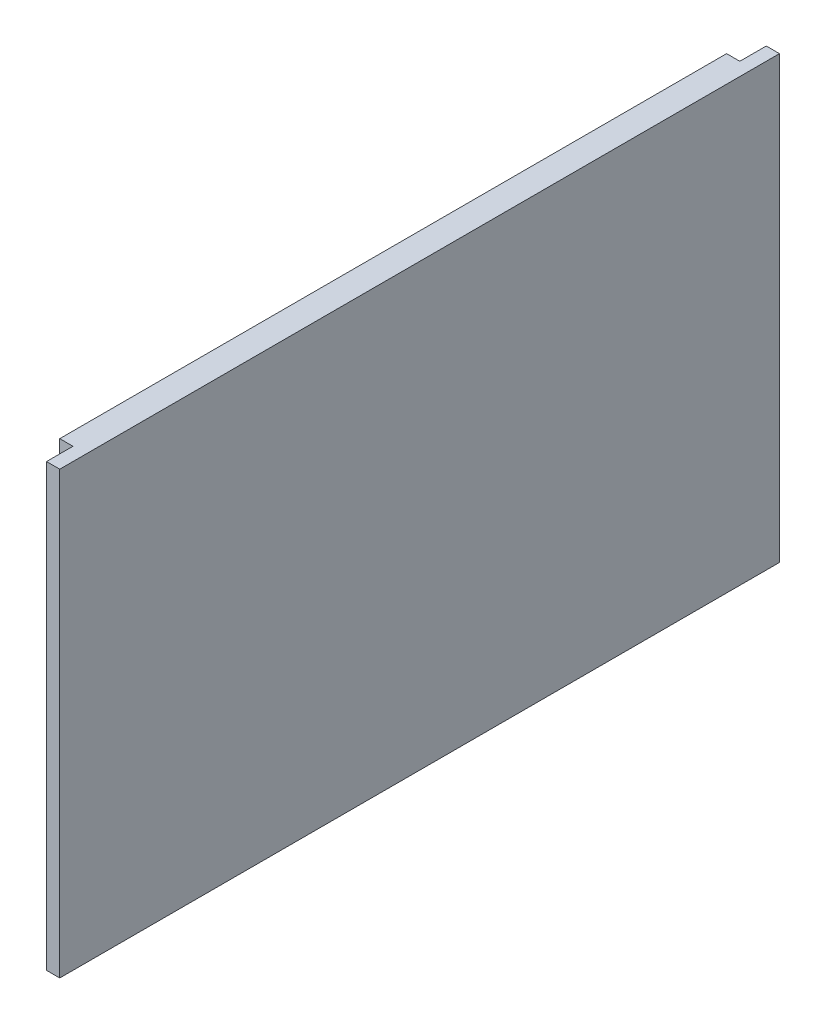
SolidWorks part; units mm, degrees
ref_plane "Front Plane" through (0, 0, 0) normal (0, 0, 1) x (1, 0, 0)
ref_plane "Top Plane" through (0, 0, 0) normal (0, 1, 0) x (1, 0, 0)
ref_plane "Right Plane" through (0, 0, 0) normal (1, 0, 0) x (0, 0, -1)
sketch "Sketch1" plane through (0, 0, 0) normal (1, 0, 0) x (0, 0, -1)
  line L1 (0, 0) -> (490, 0)
  line L2 (0, 0) -> (0, 300)
  line L3 (0, 300) -> (490, 300)
  line L4 (490, 0) -> (490, 300)
  dimension "D1" = 490
  dimension "D2" = 300
extrude "Boss-Extrude1" add sketch "Sketch1" along normal blind 18
sketch "Sketch5" plane through (0, 0, 0) normal (0, 0, 1) x (1, 0, 0)
  line L0 (18, 0) -> (0, 0) construction
  line L1 (0, 300) -> (9, 300)
  line L2 (0, 300) -> (0, 0)
  line L3 (0, 0) -> (9, 0)
  line L4 (9, 300) -> (9, 0)
  dimension "D1" = 9
extrude "Cut-Extrude1" cut sketch "Sketch5" against normal blind 18
sketch "Sketch6" plane through (0, 0, 0) normal (-1, 0, 0) x (0, 0, 1)
  line L0 (-18, 0) -> (-490, 0) construction
  line L1 (-490, 300) -> (-472, 300)
  line L2 (-490, 300) -> (-490, 0)
  line L3 (-490, 0) -> (-472, 0)
  line L4 (-472, 300) -> (-472, 0)
  dimension "D1" = 18
extrude "Cut-Extrude3" cut sketch "Sketch6" against normal blind 9
